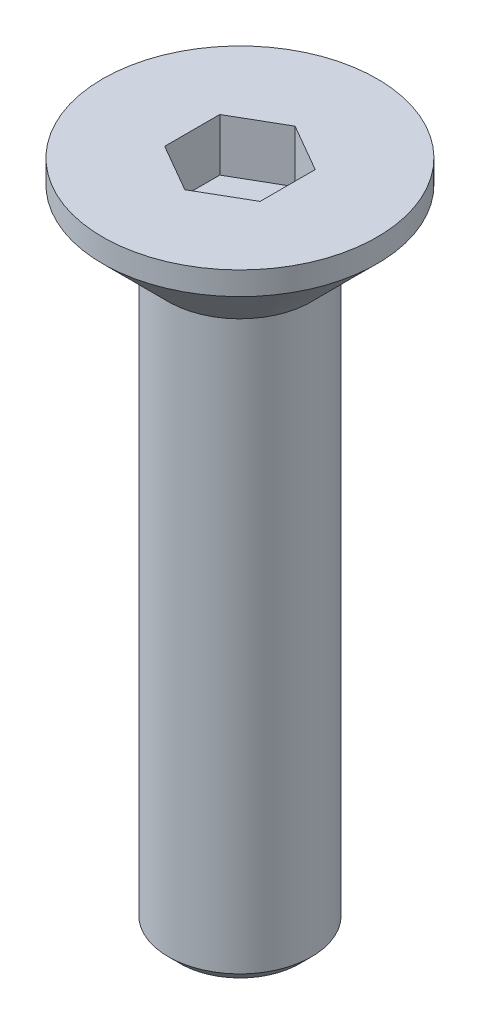
SolidWorks part; units mm, degrees
material "ASTM A36 Steel"
ref_plane "Front Plane" through (0, 0, 0) normal (0, 0, 1) x (1, 0, 0)
ref_plane "Top Plane" through (0, 0, 0) normal (0, 1, 0) x (1, 0, 0)
ref_plane "Right Plane" through (0, 0, 0) normal (1, 0, 0) x (0, 0, -1)
sketch "Sketch1" plane through (0, 0, 0) normal (0, 0, 1) x (1, 0, 0)
  line L0 (0, 0) -> (0, -14)
  line L1 (0, 0) -> (-2.875, 0)
  line L2 (-2.875, -0.485) -> (-1.5, -1.86)
  line L3 (-1.5, -1.86) -> (-1.5, -13.75)
  line L4 (-1.25, -14) -> (0, -14)
  line L5 (-2.875, 0) -> (-2.875, -0.485)
  line L6 (-1.5, -13.75) -> (-1.25, -14)
  point P6 (-1.5, -14)
  dimension "D1" = 1.86
  dimension "D2" = 2.875
  dimension "D3" = 1.5
  dimension "D4" = 45
  dimension "D5" = 14
revolve "Revolve1" add sketch "Sketch1" angle 360 about L0
sketch "Sketch2" plane through (0, 0, 0) normal (0, 1, 0) x (1, 0, 0)
  line L1 (-1, 0.5774) -> (-1, -0.5774)
  line L2 (-1, -0.5774) -> (0, -1.1547)
  line L3 (0, -1.1547) -> (1, -0.5774)
  line L4 (1, -0.5774) -> (1, 0.5774)
  line L5 (1, 0.5774) -> (0, 1.1547)
  line L6 (0, 1.1547) -> (-1, 0.5774)
  circle A0 centre (0, 0) radius 1 construction
  dimension "D1" = 2
extrude "Cut-Extrude1" cut sketch "Sketch2" against normal blind 1.1
